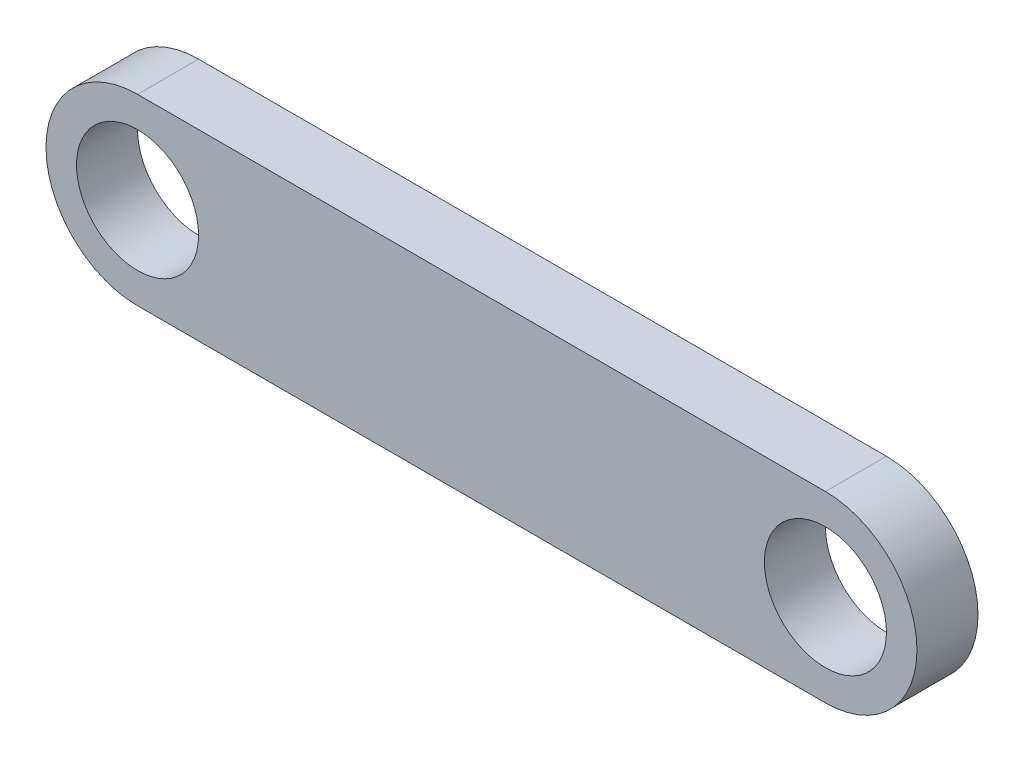
SolidWorks part; units mm, degrees
ref_plane "Front Plane" through (0, 0, 0) normal (0, 0, 1) x (1, 0, 0)
ref_plane "Top Plane" through (0, 0, 0) normal (0, 1, 0) x (1, 0, 0)
ref_plane "Right Plane" through (0, 0, 0) normal (1, 0, 0) x (0, 0, -1)
sketch "Sketch1" plane through (0, 0, 0) normal (0, 0, 1) x (1, 0, 0)
  line L0 (0, 0) -> (-11.2709, 0) construction
  line L1 (0, -1.5) -> (-11.2709, -1.5)
  line L2 (0, 1.5) -> (-11.2709, 1.5)
  arc A0 (0, -1.5) -> (0, 1.5) centre (0, 0) ccw
  arc A1 (-11.2709, 1.5) -> (-11.2709, -1.5) centre (-11.2709, 0) ccw
  circle A2 centre (-11.2709, 0) radius 1
  circle A3 centre (0, 0) radius 1
  point P3 (-5.6354, 0)
  dimension "D2" = 1.5
  dimension "D3" = 2
  dimension "D4" = 2
  dimension "D1" = 11.2709
extrude "Boss-Extrude1" add sketch "Sketch1" along normal mid plane 1
